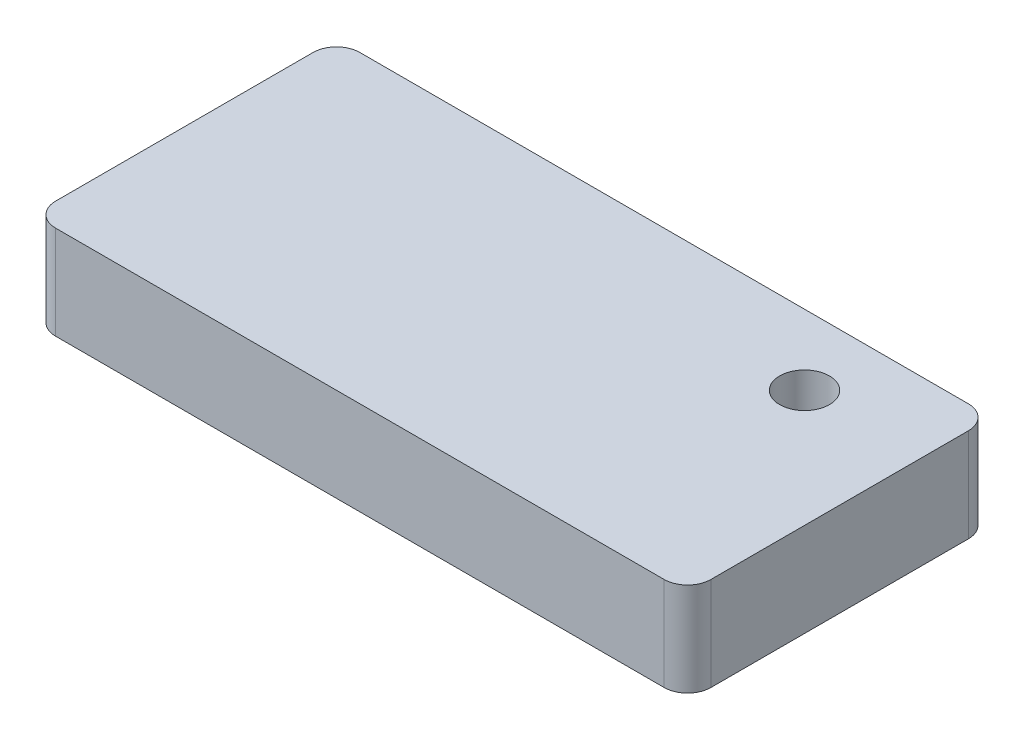
SolidWorks part; units mm, degrees
material "PE High Density"
ref_plane "Front Plane" through (0, 0, 0) normal (0, 0, 1) x (1, 0, 0)
ref_plane "Top Plane" through (0, 0, 0) normal (0, 1, 0) x (1, 0, 0)
ref_plane "Right Plane" through (0, 0, 0) normal (1, 0, 0) x (0, 0, -1)
sketch "Sketch1" plane through (0, 0, 0) normal (0, 1, 0) x (1, 0, 0)
  line L1 (0, 0) -> (88.9, 0)
  line L2 (0, 0) -> (0, 41.275)
  line L3 (0, 41.275) -> (88.9, 41.275)
  line L4 (88.9, 0) -> (88.9, 41.275)
  dimension "D1" = 41.275
  dimension "D2" = 88.9
extrude "Boss-Extrude1" add sketch "Sketch1" along normal blind 12.7
hole_wizard "1/4 Clearance Hole1" positions "Sketch2" profile "Sketch3" hole size "1/4" standard "ANSI Inch" end condition through all
sketch "Sketch2" plane through (0, 12.7, 0) normal (0, 1, 0) x (1, 0, 0)
  line L0 (0, 0) -> (88.9, 0) construction
  line L1 (0, 41.275) -> (0, 0) construction
  line L2 (-3.175, 0) -> (-3.175, 41.275) construction
  line L3 (88.9, 41.275) -> (0, 41.275) construction
  point P0 (73.025, 31.75)
  dimension "D1" = 31.75
  dimension "D2" = 73.025
  dimension "D3" = 76.2
sketch "Sketch3" plane through (73.025, 12.7, -31.75) normal (1, 0, 0) x (0, 0, 1)
  line L0 (0, 0) -> (0, 12.7)
  line L1 (0, 12.7) -> (3.3782, 12.7)
  line L2 (3.3782, 12.7) -> (3.3782, 0)
  line L5 (3.3782, 0) -> (0, 0)
  line L11 (0, -6.35) -> (0, 107.95) construction
  dimension "Thru Hole Dia." = 6.7564
  dimension "Thru Hole Depth" = 12.7
fillet "Fillet1" radius 3.175 4 edges at (88.9, 6.35, 0) (88.9, 6.35, -41.275) (0, 6.35, -41.275) (0, 6.35, 0)
